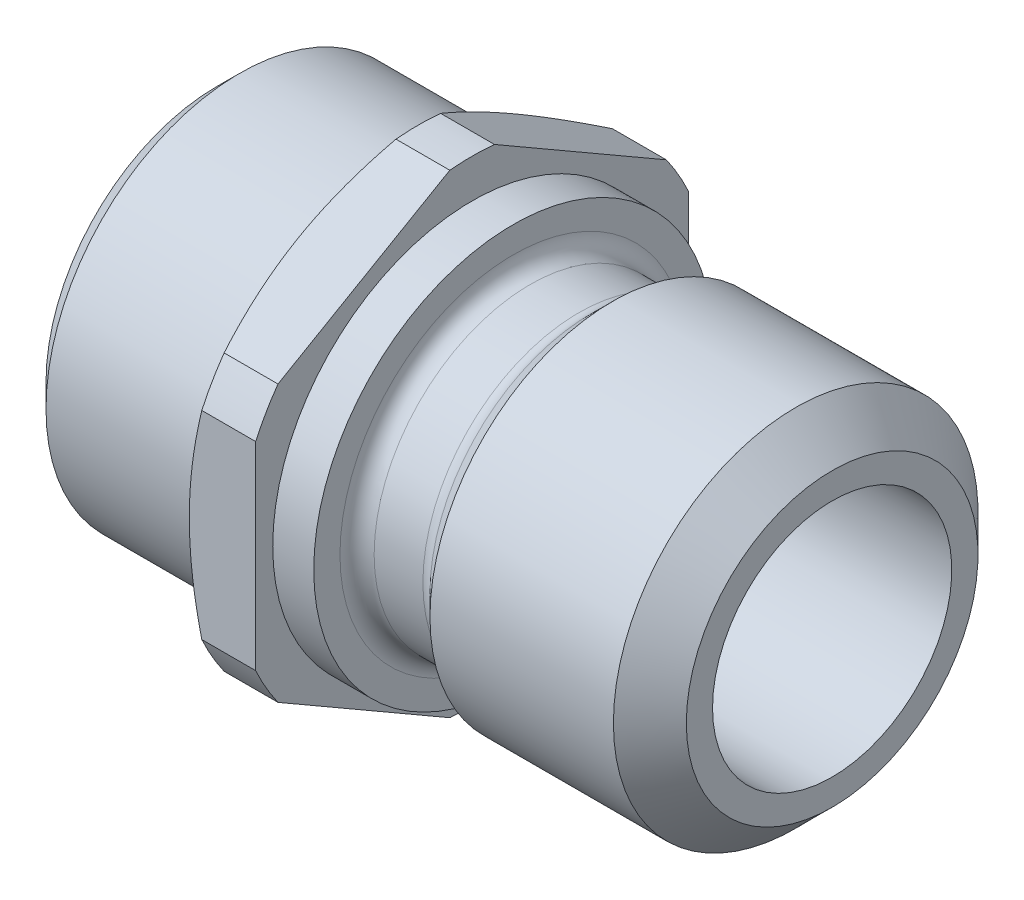
SolidWorks part; units mm, degrees
material "Алюминиевая бронза"
ref_plane "Спереди" through (0, 0, 0) normal (0, 0, 1) x (1, 0, 0)
ref_plane "Сверху" through (0, 0, 0) normal (0, 1, 0) x (1, 0, 0)
ref_plane "Справа" through (0, 0, 0) normal (1, 0, 0) x (0, 0, -1)
sketch "Эскиз1" plane through (0, 0, 0) normal (0, 0, 1) x (1, 0, 0)
  line L0 (0, 0) -> (102.1649, 0) construction
  line L1 (0, 3) -> (0, 7.5)
  line L2 (1, 8.5) -> (8, 8.5)
  line L3 (8, 8.5) -> (8, 10.45)
  line L4 (8, 10.45) -> (13, 10.45)
  line L5 (13, 10.45) -> (13, 7.6)
  line L6 (13.75, 6.85) -> (15.8893, 6.85)
  line L7 (16.4197, 7.0697) -> (17.35, 8)
  line L8 (17.35, 8) -> (25.4, 8)
  line L9 (25.4, 8) -> (27, 6.4)
  line L10 (27, 6.4) -> (27, 5.25)
  line L11 (27, 5.25) -> (4, 5.25)
  line L12 (3, 4.25) -> (3, 3)
  line L13 (3, 3) -> (0, 3)
  line L14 (0, 7.5) -> (1, 8.5)
  arc A0 (15.8893, 6.85) -> (16.4197, 7.0697) centre (15.8893, 7.6) ccw
  arc A1 (13, 7.6) -> (13.75, 6.85) centre (13.75, 7.6) ccw
  arc A2 (4, 5.25) -> (3, 4.25) centre (4, 4.25) ccw
  point P4 (0, 8.5)
  point P18 (16.2, 6.85)
  point P21 (13, 6.85)
  point P24 (3, 5.25)
  dimension "D14" = 0.75
  dimension "D15" = 1
  dimension "D1" = 6
  dimension "D2" = 17
  dimension "D3" = 10.5
  dimension "D4" = 16
  dimension "D5" = 13.7
  dimension "D6" = 45
  dimension "D7" = 1.6
  dimension "D8" = 3.2
  dimension "D9" = 5
  dimension "D10" = 8
  dimension "D11" = 27
  dimension "D12" = 24
  dimension "D13" = 20.9
  dimension "D16" = 1
  dimension "D17" = 45
revolve "Повернуть1" add sketch "Эскиз1" angle 360 about L0
cosmetic thread "Условное изображение резьбы1" parameters "D2"=14.344
sketch "Эскиз2" plane through (8, 0, 0) normal (-1, 0, 0) x (0, 0, 1)
  line L1 (0, 10.9697) -> (-9.5, 5.4848)
  line L2 (-9.5, 5.4848) -> (-9.5, -5.4848)
  line L3 (-9.5, -5.4848) -> (0, -10.9697)
  line L4 (0, -10.9697) -> (9.5, -5.4848)
  line L5 (9.5, -5.4848) -> (9.5, 5.4848)
  line L6 (9.5, 5.4848) -> (0, 10.9697)
  circle A0 centre (0, 0) radius 9.5 construction
  dimension "D1" = 19
extrude "Вырез-Вытянуть1" cut sketch "Эскиз2" against normal through all flip side to cut
sketch "Эскиз3" plane through (8, 0, 0) normal (-1, 0, 0) x (0, 0, 1)
  circle A0 centre (0, 0) radius 9
  dimension "D1" = 18
extrude "Вырез-Вытянуть2" cut sketch "Эскиз3" against normal through all draft 60 flip side to cut
sketch "Эскиз4" plane through (13, 0, 0) normal (1, 0, 0) x (0, 0, -1)
  circle A0 centre (0, 0) radius 8.75
  dimension "D1" = 17.5
extrude "Вырез-Вытянуть3" cut sketch "Эскиз4" against normal blind 1.8 flip side to cut
